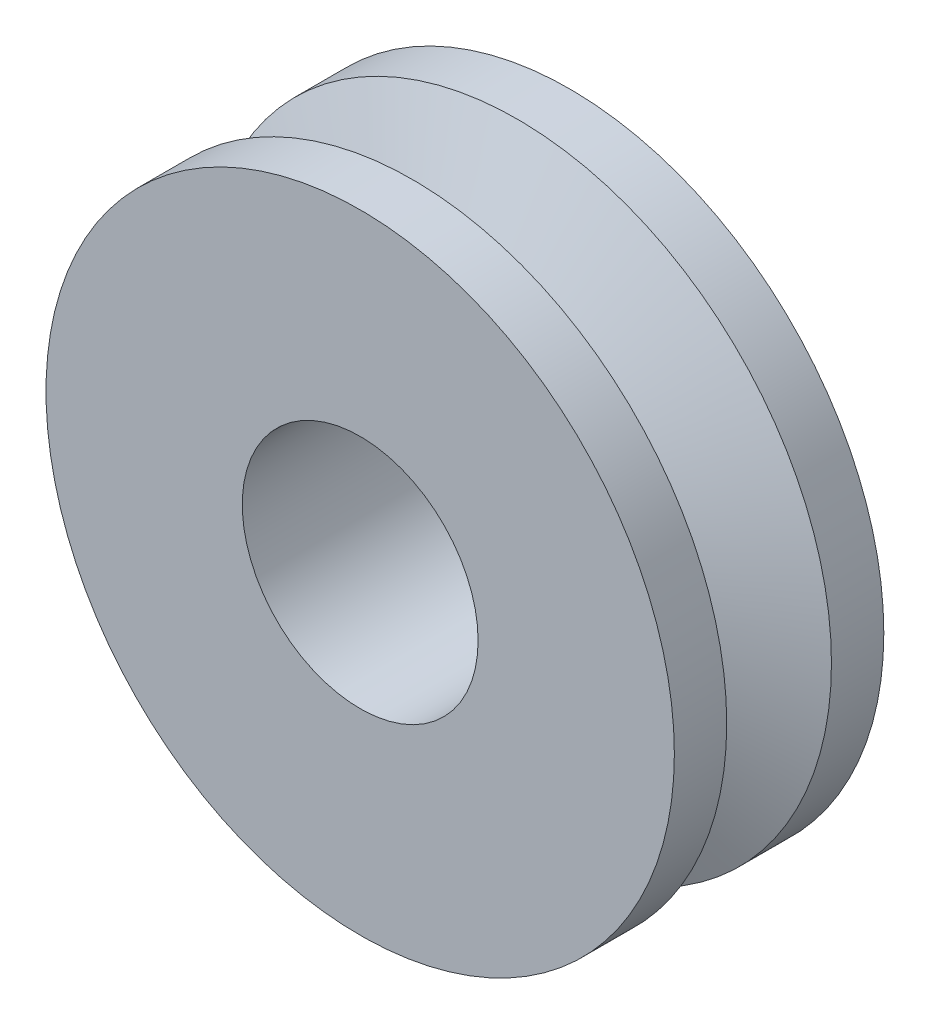
SolidWorks part; units mm, degrees
ref_plane "Ön Düzlem" through (0, 0, 0) normal (0, 0, 1) x (1, 0, 0)
ref_plane "Üst Düzlem" through (0, 0, 0) normal (0, 1, 0) x (1, 0, 0)
ref_plane "Sağ Düzlem" through (0, 0, 0) normal (1, 0, 0) x (0, 0, -1)
sketch "Çizim1" plane through (0, 0, 0) normal (1, 0, 0) x (0, 0, -1)
  line L0 (-13.1988, 0) -> (20.5812, 0) construction
  line L1 (-2.5, 15) -> (0, 8.9645)
  line L2 (-5, 15) -> (-2.5, 15)
  line L3 (-5, 15) -> (-5, 5.63)
  line L4 (-5, 5.63) -> (5, 5.63)
  line L5 (5, 15) -> (5, 5.63)
  line L6 (0, 8.9645) -> (2.5, 15)
  line L7 (2.5, 15) -> (5, 15)
  point P9 (0, 5.63)
  dimension "D1" = 5.63
  dimension "D2" = 15
  dimension "D3" = 2.5
  dimension "D4" = 2.5
  dimension "D5" = 10
  dimension "D6" = 45
revolve "Döndür1" add sketch "Çizim1" angle 360 about L0
